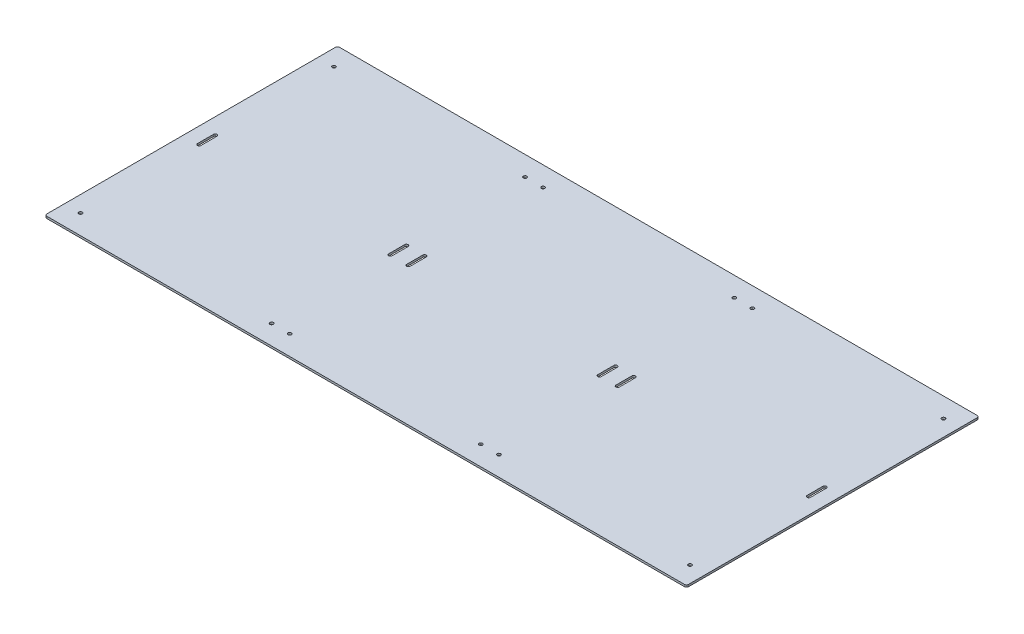
SolidWorks part; units mm, degrees
material "PC High Viscosity"
ref_plane "Front Plane" through (0, 0, 0) normal (0, 0, 1) x (1, 0, 0)
ref_plane "Top Plane" through (0, 0, 0) normal (0, 1, 0) x (1, 0, 0)
ref_plane "Right Plane" through (0, 0, 0) normal (1, 0, 0) x (0, 0, -1)
sketch "Sketch1" plane through (0, 0, 0) normal (0, 1, 0) x (1, 0, 0)
  line L0 (654.05, 862.0125) -> (711.2, 862.0125) construction
  line L1 (6.35, 0) -> (2019.3, 0)
  line L2 (0, 6.35) -> (0, 917.575)
  line L3 (6.35, 923.925) -> (2019.3, 923.925)
  line L4 (2025.65, 6.35) -> (2025.65, 917.575)
  line L5 (654.05, 862.0125) -> (654.05, 61.9125) construction
  line L6 (1371.6, 862.0125) -> (1314.45, 862.0125) construction
  line L7 (1371.6, 862.0125) -> (1371.6, 61.9125) construction
  line L8 (50.8, 487.3625) -> (50.8, 436.5625) construction
  line L9 (56.1578, 487.3625) -> (56.1578, 436.5625)
  line L10 (45.4422, 487.3625) -> (45.4422, 436.5625)
  line L11 (654.05, 487.3625) -> (654.05, 436.5625) construction
  line L12 (659.4078, 487.3625) -> (659.4078, 436.5625)
  line L13 (648.6922, 487.3625) -> (648.6922, 436.5625)
  line L14 (711.2, 487.3625) -> (711.2, 436.5625) construction
  line L15 (716.5578, 487.3625) -> (716.5578, 436.5625)
  line L16 (705.8422, 487.3625) -> (705.8422, 436.5625)
  line L17 (1012.825, 923.925) -> (1012.825, -49.4513) construction
  line L18 (1974.85, 487.3625) -> (1974.85, 436.5625) construction
  line L19 (1969.4922, 487.3625) -> (1969.4922, 436.5625)
  line L20 (1980.2078, 487.3625) -> (1980.2078, 436.5625)
  line L21 (1314.45, 487.3625) -> (1314.45, 436.5625) construction
  line L22 (1309.0922, 487.3625) -> (1309.0922, 436.5625)
  line L23 (1319.8078, 487.3625) -> (1319.8078, 436.5625)
  line L24 (1371.6, 487.3625) -> (1371.6, 436.5625) construction
  line L25 (1366.2422, 487.3625) -> (1366.2422, 436.5625)
  line L26 (1376.9578, 487.3625) -> (1376.9578, 436.5625)
  arc A0 (2019.3, 923.925) -> (2025.65, 917.575) centre (2019.3, 917.575) cw
  arc A1 (2019.3, 0) -> (2025.65, 6.35) centre (2019.3, 6.35) ccw
  arc A2 (6.35, 0) -> (0, 6.35) centre (6.35, 6.35) cw
  arc A3 (0, 917.575) -> (6.35, 923.925) centre (6.35, 917.575) cw
  circle A4 centre (50.8, 862.0125) radius 5.3578
  circle A5 centre (1974.85, 862.0125) radius 5.3578
  circle A6 centre (1974.85, 61.9125) radius 5.3578
  circle A8 centre (50.8, 61.9125) radius 5.3578
  circle A10 centre (654.05, 862.0125) radius 5.3578
  circle A11 centre (1371.6, 862.0125) radius 5.3578
  circle A12 centre (711.2, 862.0125) radius 5.3578
  circle A13 centre (711.2, 61.9125) radius 5.3578
  circle A15 centre (654.05, 61.9125) radius 5.3578
  circle A17 centre (1314.45, 862.0125) radius 5.3578
  circle A18 centre (1314.45, 61.9125) radius 5.3578
  circle A20 centre (1371.6, 61.9125) radius 5.3578
  arc A22 (56.1578, 487.3625) -> (45.4422, 487.3625) centre (50.8, 487.3625) ccw
  arc A23 (45.4422, 436.5625) -> (56.1578, 436.5625) centre (50.8, 436.5625) ccw
  arc A24 (659.4078, 487.3625) -> (648.6922, 487.3625) centre (654.05, 487.3625) ccw
  arc A25 (648.6922, 436.5625) -> (659.4078, 436.5625) centre (654.05, 436.5625) ccw
  arc A26 (716.5578, 487.3625) -> (705.8422, 487.3625) centre (711.2, 487.3625) ccw
  arc A27 (705.8422, 436.5625) -> (716.5578, 436.5625) centre (711.2, 436.5625) ccw
  arc A28 (1969.4922, 487.3625) -> (1980.2078, 487.3625) centre (1974.85, 487.3625) cw
  arc A29 (1980.2078, 436.5625) -> (1969.4922, 436.5625) centre (1974.85, 436.5625) cw
  arc A30 (1309.0922, 487.3625) -> (1319.8078, 487.3625) centre (1314.45, 487.3625) cw
  arc A31 (1319.8078, 436.5625) -> (1309.0922, 436.5625) centre (1314.45, 436.5625) cw
  arc A32 (1366.2422, 487.3625) -> (1376.9578, 487.3625) centre (1371.6, 487.3625) cw
  arc A33 (1376.9578, 436.5625) -> (1366.2422, 436.5625) centre (1371.6, 436.5625) cw
  point P7 (2025.65, 923.925)
  point P12 (0, 0)
  point P15 (0, 923.925)
  point P29 (50.8, 461.9625)
  point P39 (711.2, 461.9625)
  point P52 (654.05, 461.9625)
  point P69 (1974.85, 461.9625)
  point P76 (1314.45, 461.9625)
  point P83 (1371.6, 461.9625)
  dimension "D3" = 6.35
  dimension "D6" = 10.7156
  dimension "D11" = 10.7156
  dimension "D13" = 10.7156
  dimension "D14" = 61.9125
  dimension "D15" = 50.8
  dimension "D16" = 800.1
  dimension "D17" = 50.8
  dimension "D18" = 2
  dimension "D22" = 400.05
  dimension "D31" = 50.8
  dimension "D32" = 1012.825
  dimension "D1" = 2025.65
  dimension "D2" = 923.925
  dimension "D4" = 50.8
  dimension "D5" = 61.9125
  dimension "D9" = 603.25
  dimension "D10" = 61.9125
  dimension "D12" = 603.25
  dimension "D20" = 57.15
  dimension "D21" = 800.1
  dimension "D25" = 90
  dimension "D26" = 57.15
  dimension "D27" = 800.1
  dimension "D28" = 50.8
  dimension "D30" = 374.65
  dimension "D7" = 2
  dimension "D8" = 2
  dimension "D19" = 2
  dimension "D23" = 2
  dimension "D24" = 2
  dimension "D29" = 2
extrude "Boss-Extrude1" add sketch "Sketch1" along normal blind 6.35
